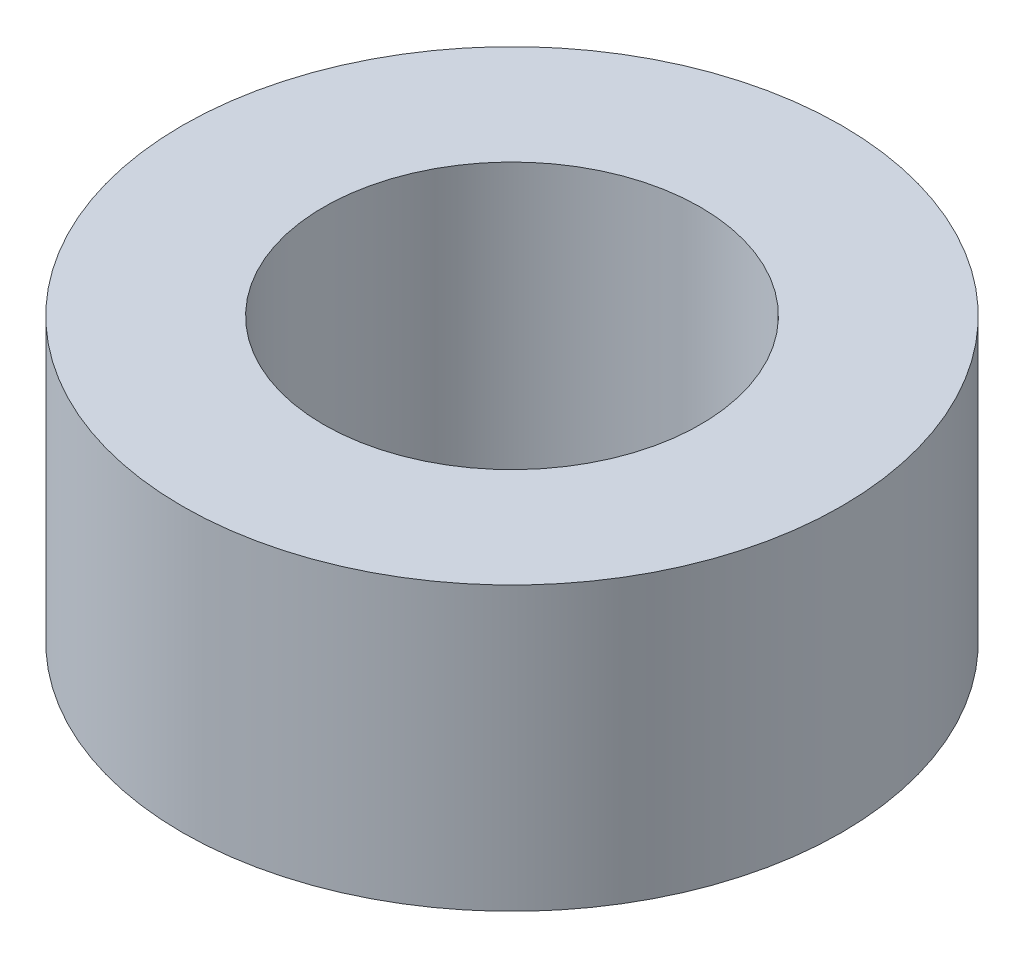
SolidWorks part; units mm, degrees
material "尼龙 101"
ref_plane "前视基准面" through (0, 0, 0) normal (0, 0, 1) x (1, 0, 0)
ref_plane "上视基准面" through (0, 0, 0) normal (0, 1, 0) x (1, 0, 0)
ref_plane "右视基准面" through (0, 0, 0) normal (1, 0, 0) x (0, 0, -1)
sketch "草图1" plane through (0, 0, 0) normal (0, 1, 0) x (1, 0, 0)
  circle A0 centre (0, 0) radius 3.5
  circle A1 centre (0, 0) radius 2
  dimension "D1" = 4
  dimension "D2" = 7
extrude "凸台-拉伸1" add sketch "草图1" along normal blind 3
